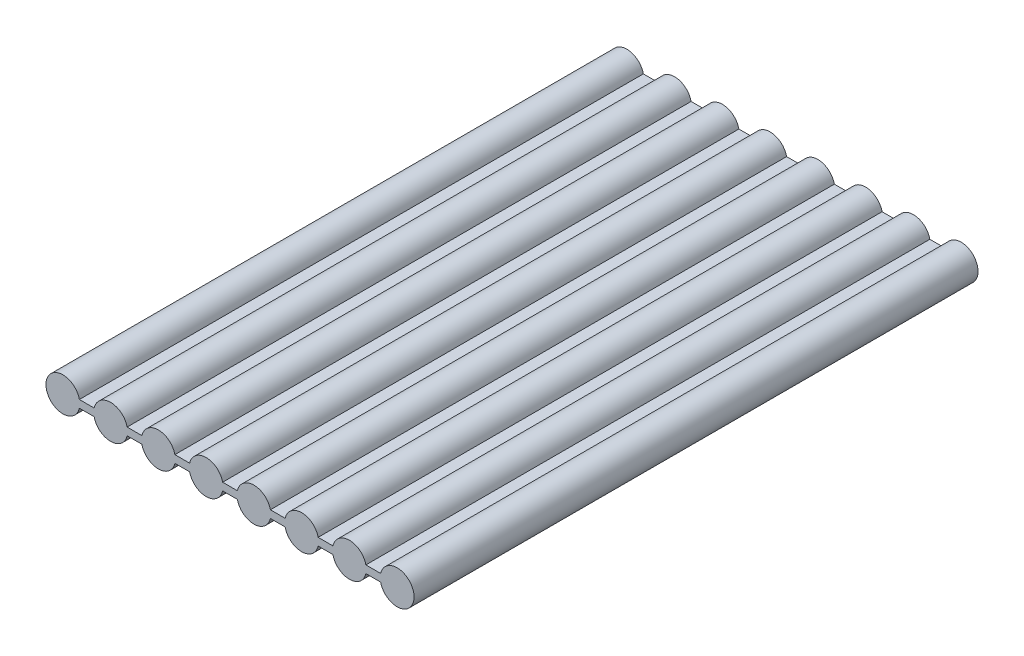
SolidWorks part; units mm, degrees
ref_plane "Plan de face" through (0, 0, 0) normal (0, 0, 1) x (1, 0, 0)
ref_plane "Plan de dessus" through (0, 0, 0) normal (0, 1, 0) x (1, 0, 0)
ref_plane "Plan de droite" through (0, 0, 0) normal (1, 0, 0) x (0, 0, -1)
sketch "Esquisse1" plane through (0, 0, 0) normal (0, 0, 1) x (1, 0, 0)
  line L0 (-4.445, 0) -> (4.445, 0) construction
  circle A0 centre (-4.445, 0) radius 0.45
  point P2 (0, 0)
  dimension "D1" = 0.9
  dimension "D2" = 8.89
extrude "Boss.-Extru.1" add sketch "Esquisse1" along normal mid plane 15
pattern_linear "Répétition linéaire1" count 8 spacing 1.27 along (1, 0, 0) of "Boss.-Extru.1"
sketch "Esquisse2" plane through (0, 0, 0) normal (0, 0, 1) x (1, 0, 0)
  line L0 (-4.0063, 0.1) -> (-3.6137, 0.1)
  line L1 (0, 0) -> (0.6623, 0) construction
  line L2 (-4.0063, -0.1) -> (-3.6137, -0.1)
  circle A0 centre (-4.445, 0) radius 0.45 construction
  circle A1 centre (-3.175, 0) radius 0.45 construction
  arc A2 (-3.6137, 0.1) -> (-3.6137, -0.1) centre (-3.175, 0) ccw
  arc A3 (-4.0063, -0.1) -> (-4.0063, 0.1) centre (-4.445, 0) ccw
  dimension "D1" = 0.2
extrude "Boss.-Extru.2" add sketch "Esquisse2" along normal mid plane 15
pattern_linear "Répétition linéaire2" count 7 spacing 1.27 along (1, 0, 0) of "Boss.-Extru.2"
equation "\"conductors\"= 8"
equation "\"D1@Répétition linéaire1\"=\"conductors\""
equation "\"D1@Répétition linéaire2\"=\"conductors\"-1"
equation "\"D2@Esquisse1\"=(\"conductors\"-1)*1.27"
